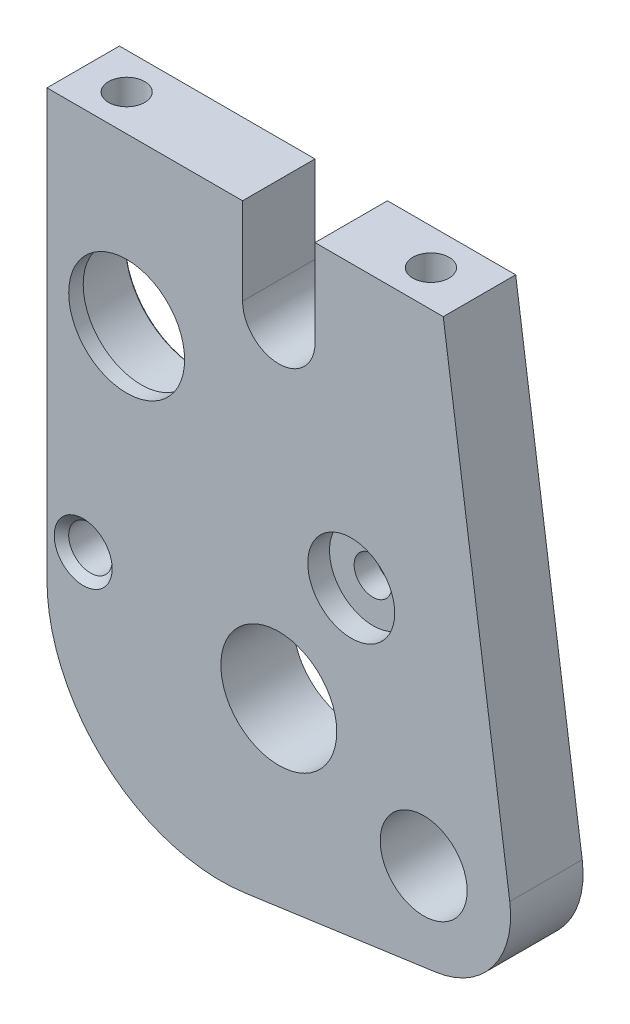
SolidWorks part; units mm, degrees
material "45"
ref_plane "前视基准面" through (0, 0, 0) normal (0, 0, 1) x (1, 0, 0)
ref_plane "上视基准面" through (0, 0, 0) normal (0, 1, 0) x (1, 0, 0)
ref_plane "右视基准面" through (0, 0, 0) normal (1, 0, 0) x (0, 0, -1)
sketch "草图1" plane through (0, 0, 0) normal (0, 0, 1) x (1, 0, 0)
  line L1 (0, 0) -> (34, 0)
  line L2 (0, 0) -> (0, -39.5)
  line L3 (0, -39.5) -> (34, -39.5)
  line L4 (34, 0) -> (34, -39.5)
  dimension "D1" = 34
  dimension "D2" = 39.5
  dimension "D3" = 90
extrude "拉伸1" add sketch "草图1" along normal blind 5
fillet "圆角1" radius 12 1 edges at (0, -39.5, 2.5)
sketch "草图2" plane through (0, 0, 5) normal (0, 0, 1) x (1, 0, 0)
  line L0 (0, 0) -> (0, -27.5) construction
  line L1 (34, 0) -> (0, 0) construction
  circle A0 centre (26, -33.5) radius 3
  dimension "D2" = 33.5
  dimension "D3" = 6
  dimension "D1" = 26
extrude "拉伸2" cut sketch "草图2" against normal up to surface (5 mm away) up to face at (15.5029, -21.7971, 0)
sketch "草图3" plane through (0, 0, 0) normal (0, 0, -1) x (-1, 0, 0)
  line L0 (-34, 0) -> (0, 0) construction
  line L1 (0, 0) -> (0, -27.5) construction
  circle A0 centre (-5.5, -11.5) radius 4
  dimension "D1" = 8
  dimension "D3" = 5.5
  dimension "D2" = 11.5
extrude "拉伸3" cut sketch "草图3" against normal up to surface (5 mm away) up to face at (29, -33.5, 5)
sketch "草图4" plane through (0, 0, 0) normal (0, 0, -1) x (-1, 0, 0)
  circle A0 centre (-5.5, -11.5) radius 5
  dimension "D1" = 10
extrude "拉伸4" cut sketch "草图4" against normal blind 4
chamfer "倒角2" [suppressed] distance 0.5 angle 45
sketch "草图7" plane through (0, 0, 0) normal (0, 0, -1) x (-1, 0, 0)
  line L0 (-12, -39.5) -> (-34, -39.5) construction
  line L1 (-26, -39.5) -> (-34, -39.5)
  line L2 (-31.9416, -32.665) -> (-27.3508, 0)
  line L3 (-34, 0) -> (0, 0) construction
  line L4 (-34, -39.5) -> (-34, 0)
  line L5 (-34, 0) -> (-27.3508, 0)
  arc A0 (-31.9416, -32.665) -> (-26, -39.5) centre (-26, -33.5) ccw
  dimension "D1" = 6
  dimension "D2" = 8
extrude "拉伸5" cut sketch "草图7" against normal blind 10
sketch "Sketch1" plane through (0, 0, 5) normal (0, 0, 1) x (1, 0, 0)
  line L0 (26.835, -39.4416) -> (13.6701, -41.2918)
  line L1 (12, -39.5) -> (26, -39.5) construction
  line L2 (0, -26.5198) -> (0, -29.4086)
  line L3 (0, 0) -> (0, -27.5) construction
  line L4 (26, -33.5) -> (29.4415, -38.4149) construction
  line L5 (29.4415, -38.4149) -> (0, -26.5198)
  arc A0 (26, -39.5) -> (31.9416, -32.665) centre (26, -33.5) ccw construction
  arc A1 (26.835, -39.4416) -> (29.4415, -38.4149) centre (26, -33.5) ccw
  arc A2 (13.6701, -41.2918) -> (0, -29.4086) centre (12, -29.4086) cw
  dimension "D2" = 12
  dimension "D1" = 8
  dimension "D3" = 55
  dimension "D4" = 22
extrude "Extrude1" add sketch "Sketch1" against normal up to surface (5 mm away) up to face at (0.5, -11.5, 0)
sketch "草图8" plane through (0, 0, 5) normal (0, 0, 1) x (1, 0, 0)
  line L1 (0, 0) -> (0, -29.4086) construction
  line L2 (27.3508, 0) -> (0, 0) construction
  circle A0 centre (2.5, -26.5) radius 1.5
  dimension "D1" = 3
  dimension "D3" = 2.5
  dimension "D2" = 26.5
extrude "拉伸6" cut sketch "草图8" against normal blind 4.5
sketch "Sketch9" plane through (0, 0, 0.5) normal (0, 0, 1) x (1, 0, 0)
  line L0 (2.5, -26.5) -> (1.5, -26.5) construction
  circle A0 centre (1.5, -26.5) radius 0.5
  dimension "D2" = 1
  dimension "D1" = 1
extrude "Extrude5" cut sketch "Sketch9" against normal through all
sketch "草图9" plane through (0, 0, 5) normal (0, 0, 1) x (1, 0, 0)
  line L0 (2.5, -26.5) -> (2.5, -22.5) construction
  line L1 (0.25, -26.5) -> (0.25, -22.5)
  line L2 (4.75, -26.5) -> (4.75, -22.5)
  line L3 (0, 0) -> (0, -29.4086) construction
  arc A0 (0.25, -26.5) -> (4.75, -26.5) centre (2.5, -26.5) ccw
  arc A1 (4.75, -22.5) -> (0.25, -22.5) centre (2.5, -22.5) ccw
  point P3 (2.5, -24.5)
  dimension "D1" = 0
  dimension "D2" = 4.5
  dimension "D3" = 4
extrude "拉伸7" cut sketch "草图9" against normal blind 0.5
sketch "草图13" plane through (0, 0, 5) normal (0, 0, 1) x (1, 0, 0)
  line L2 (0, 0) -> (0, -29.4086) construction
  line L3 (27.3508, 0) -> (0, 0) construction
  circle A1 centre (16, -28.5) radius 4
  dimension "D1" = 8
  dimension "D2" = 28.5
  dimension "D4" = 16
extrude "拉伸8" cut sketch "草图13" against normal blind 10
sketch "Sketch2" plane through (0, 0, 0) normal (0, 0, -1) x (-1, 0, 0)
  line L1 (-18, -21.9) -> (-24, -21.9)
  line L2 (-18, -21.9) -> (-18, -14.9)
  line L3 (-18, -14.9) -> (-24, -14.9)
  line L4 (-24, -21.9) -> (-24, -14.9)
  line L6 (-21, -14.9) -> (-21, -21.9) construction
  line L7 (-24, -18.4) -> (-18, -18.4) construction
  circle A0 centre (-5.5, -11.5) radius 5 construction
  circle A1 centre (-5.5, -11.5) radius 5 construction
  dimension "D1" = 15.5
  dimension "D2" = 6.9
  dimension "D3" = 7
  dimension "D4" = 6
extrude "Extrude2" cut sketch "Sketch2" against normal blind 2
sketch "Sketch3" plane through (0, 0, 5) normal (0, 0, 1) x (1, 0, 0)
  line L0 (18, -14.9) -> (24, -14.9) construction
  line L1 (18, -14.9) -> (24, -14.9)
  line L2 (24, -21.9) -> (18, -21.9) construction
  line L3 (24, -21.9) -> (18, -21.9)
  line L4 (21, -14.9) -> (21, -13.4)
  line L5 (21, -13.4) -> (21, -19.4)
  line L6 (21, -19.4) -> (21, -21.9)
  dimension "D2" = 2.5
  dimension "D1" = 6
hole_wizard "打孔尺寸(%根据)内六角圆柱头螺钉的类型1" positions "3DSketch3" profile "Sketch6" counterbore size "M2.5" standard "GB" end condition through all
sketch3d "3DSketch3"
  point P3 (21, -19.4, 5)
sketch "Sketch6" plane through (21, -19.4, 5) normal (1, 0, 0) x (0, -1, 0)
  line L0 (0, 0) -> (0, 5)
  line L1 (0, 5) -> (1.3, 5)
  line L3 (1.3, 5) -> (1.3, 1.5)
  line L4 (1.3, 1.5) -> (3, 1.5)
  line L5 (3, 1.5) -> (3, 0)
  line L7 (3, 0) -> (0, 0)
  line L11 (0, -6.35) -> (0, 107.95) construction
  dimension "通孔孔直径" = 2.6
  dimension "通孔孔深度" = 5
  dimension "柱形沉头孔直径" = 6
  dimension "柱形沉头孔深度" = 1.5
sketch "Sketch7" plane through (0, 0, 0) normal (0, 0, -1) x (-1, 0, 0)
  line L0 (-24, -14.9) -> (-24, -21.9) construction
  line L1 (-18, -21.9) -> (-18, -14.9) construction
  circle A0 centre (-24, -16.4) radius 1.5
  circle A1 centre (-18, -16.4) radius 1.5
  circle A2 centre (-24, -20.4) radius 1.5
  circle A3 centre (-18, -20.4) radius 1.5
  dimension "D1" = 3
extrude "Extrude3" cut sketch "Sketch7" against normal up to surface (2 mm away) up to face at (19.7, -19.4, 2)
sketch "Sketch8" plane through (0, 0, 0) normal (0, 0, -1) x (-1, 0, 0)
  line L0 (-13.5, -6) -> (-13.5, 0)
  line L1 (-27.3508, 0) -> (0, 0) construction
  line L2 (-13.5, 0) -> (-18.5, 0)
  line L3 (-18.5, 0) -> (-18.5, -6)
  line L4 (0, 0) -> (0, -29.4086) construction
  arc A0 (-18.5, -6) -> (-13.5, -6) centre (-16, -6) ccw
  dimension "D1" = 2.5
  dimension "D2" = 6
  dimension "D3" = 16
extrude "Extrude4" cut sketch "Sketch8" against normal through all
sketch "Sketch10" plane through (0, 0, 4.5) normal (0, 0, 1) x (1, 0, 0)
  circle A0 centre (2.5, -26.5) radius 1.5 construction
  circle A1 centre (2.5, -26.5) radius 1.5
extrude "Extrude6" cut sketch "Sketch10" against normal blind 10
chamfer "倒角5" distance 0.1 angle 45 1 edges at (0.5, -11.5, 0)
sketch "草图22" plane through (0, 0, 5) normal (0, 0, 1) x (1, 0, 0)
  line L2 (4.75, -26.5) -> (4.75, -22.5)
  line L3 (0.25, -22.5) -> (0.25, -26.5)
  line L4 (4.75, -26.5) -> (4.75, -22.5)
  line L5 (0.25, -22.5) -> (0.25, -26.5)
  circle A0 centre (2.5, -26.5) radius 1.5 construction
  circle A1 centre (2.5, -26.5) radius 1.5
  arc A2 (0.25, -26.5) -> (4.75, -26.5) centre (2.5, -26.5) ccw
  arc A3 (4.75, -22.5) -> (0.25, -22.5) centre (2.5, -22.5) ccw
  arc A4 (0.25, -26.5) -> (4.75, -26.5) centre (2.5, -26.5) ccw
  arc A5 (4.75, -22.5) -> (0.25, -22.5) centre (2.5, -22.5) ccw
  dimension "D1" = 0
extrude "凸台-拉伸1" add sketch "草图22" against normal up to surface (5 mm away) up to face at (10.6, -11.5, 0)
chamfer "倒角6" distance 0.5 angle 45 1 edges at (4, -26.5, 5)
sketch "草图5" plane through (0, 0, 0) normal (0, 1, 0) x (1, 0, 0)
  line L0 (3, -2.5) -> (24, -2.5)
  line L1 (6.75, 0) -> (6.75, -2.5) construction
  line L2 (13.5, 0) -> (0, 0) construction
  line L3 (0, -5) -> (0, 0) construction
  circle A0 centre (24, -2.5) radius 1.25
  circle A1 centre (3, -2.5) radius 1.25
  dimension "D4" = 2.5
  dimension "D5" = 2.5
  dimension "D1" = 21
  dimension "D2" = 2.5
  dimension "D3" = 3
extrude "切除-拉伸1" cut sketch "草图5" against normal blind 6
